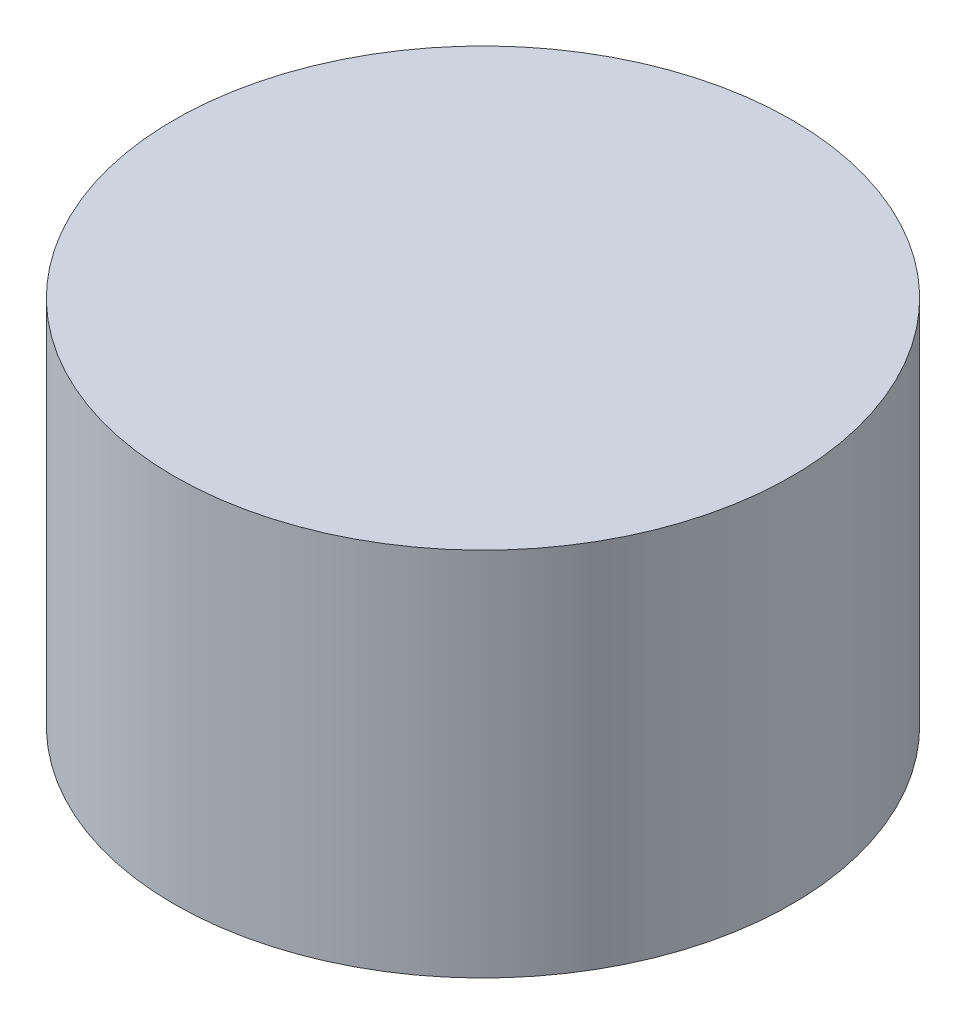
SolidWorks part; units mm, degrees
material "C (Graphite)"
ref_plane "Front Plane" through (0, 0, 0) normal (0, 0, 1) x (1, 0, 0)
ref_plane "Top Plane" through (0, 0, 0) normal (0, 1, 0) x (1, 0, 0)
ref_plane "Right Plane" through (0, 0, 0) normal (1, 0, 0) x (0, 0, -1)
sketch "Sketch1" plane through (0, 0, 0) normal (0, 1, 0) x (1, 0, 0)
  circle A0 centre (0, 0) radius 2.5
  dimension "D1" = 5
extrude "Boss-Extrude1" add sketch "Sketch1" along normal blind 3
